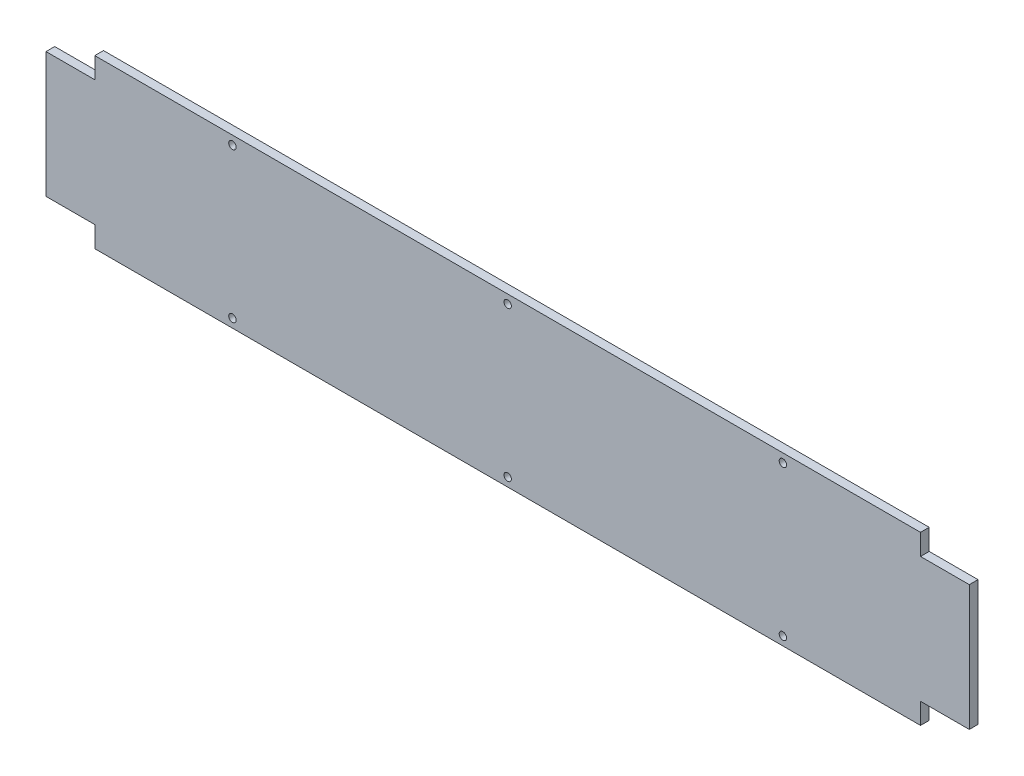
SolidWorks part; units mm, degrees
ref_plane "Front Plane" through (0, 0, 0) normal (0, 0, 1) x (1, 0, 0)
ref_plane "Top Plane" through (0, 0, 0) normal (0, 1, 0) x (1, 0, 0)
ref_plane "Right Plane" through (0, 0, 0) normal (1, 0, 0) x (0, 0, -1)
sketch "Sketch1" plane through (0, 0, 0) normal (0, 0, 1) x (1, 0, 0)
  line L1 (0, 0) -> (474, 0)
  line L2 (0, 0) -> (0, 96)
  line L3 (0, 96) -> (474, 96)
  line L4 (474, 0) -> (474, 96)
  dimension "D1" = 96
  dimension "D2" = 474
extrude "Boss-Extrude1" add sketch "Sketch1" along normal blind 5
sketch "Sketch2" plane through (0, 0, 5) normal (0, 0, 1) x (1, 0, 0)
  line L0 (474, 96) -> (0, 96) construction
  line L1 (0, 96) -> (0, 0) construction
  line L2 (168.4658, 48) -> (329.5293, 48) construction
  circle A0 centre (79, 91) radius 2.125
  circle A1 centre (237, 91) radius 2.125
  circle A2 centre (395, 91) radius 2.125
  circle A3 centre (395, 5) radius 2.125
  circle A4 centre (237, 5) radius 2.125
  circle A5 centre (79, 5) radius 2.125
  dimension "D1" = 4.25
  dimension "D2" = 4.25
  dimension "D3" = 4.25
  dimension "D4" = 5
  dimension "D5" = 79
  dimension "D6" = 158
  dimension "D7" = 158
  dimension "D8" = 48
extrude "Cut-Extrude1" cut sketch "Sketch2" against normal blind 5
sketch "Sketch3" plane through (0, 0, 5) normal (0, 0, 1) x (1, 0, 0)
  line L0 (474, 0) -> (474, 96) construction
  line L1 (474, 84) -> (502, 84)
  line L2 (474, 84) -> (474, 12)
  line L3 (474, 12) -> (502, 12)
  line L4 (502, 84) -> (502, 12)
  line L5 (0, 96) -> (0, 0) construction
  line L6 (0, 84) -> (-28, 84)
  line L7 (0, 84) -> (0, 12)
  line L8 (0, 12) -> (-28, 12)
  line L9 (-28, 84) -> (-28, 12)
  line L10 (0, 0) -> (474, 0) construction
  line L11 (474, 96) -> (0, 96) construction
  dimension "D1" = 28
  dimension "D2" = 12
  dimension "D3" = 12
  dimension "D4" = 12
  dimension "D5" = 12
  dimension "D6" = 28
extrude "Boss-Extrude2" add sketch "Sketch3" against normal blind 5
